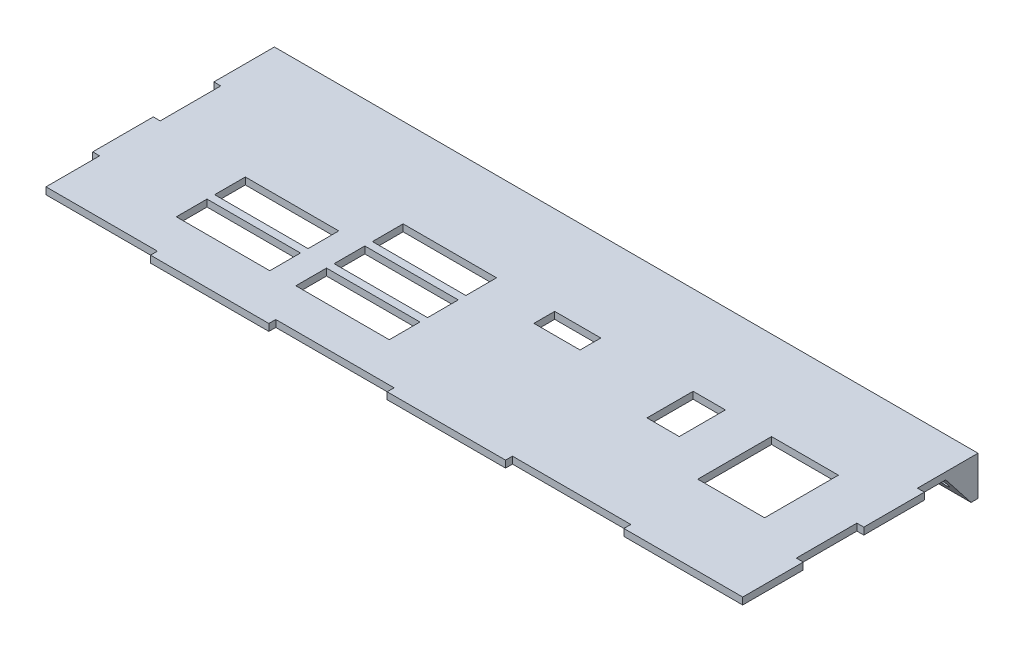
SolidWorks part; units mm, degrees
ref_plane "Спереди" through (0, 0, 0) normal (0, 0, 1) x (1, 0, 0)
ref_plane "Сверху" through (0, 0, 0) normal (0, 1, 0) x (1, 0, 0)
ref_plane "Справа" through (0, 0, 0) normal (1, 0, 0) x (0, 0, -1)
other "Configuration Table"
sketch "Эскиз1" plane through (0, 0, 0) normal (0, 1, 0) x (1, 0, 0)
  line L0 (-121.424, 15.1446) -> (-121.424, 41.3946)
  line L1 (-118.424, -63.6054) -> (186.576, -63.6054)
  line L2 (-121.424, -37.3554) -> (-121.424, -11.1054)
  line L3 (-121.424, 41.3946) -> (183.576, 41.3946)
  line L4 (186.576, -63.6054) -> (186.576, -37.3554)
  line L5 (-118.424, -62.7765) -> (183.576, 97.3135) construction
  line L6 (-121.424, 41.3946) -> (186.576, -63.6054) construction
  line L11 (-121.424, 15.1446) -> (-118.424, 15.1446)
  line L13 (-121.424, -11.1054) -> (-118.424, -11.1054)
  line L14 (-118.424, 15.1446) -> (-118.424, -11.1054)
  line L15 (-121.424, -37.3554) -> (-118.424, -37.3554)
  line L18 (-118.424, -37.3554) -> (-118.424, -63.6054)
  line L21 (186.576, 15.1446) -> (183.576, 15.1446)
  line L22 (183.576, 41.3946) -> (183.576, 15.1446)
  line L23 (186.576, -37.3554) -> (183.576, -37.3554)
  line L25 (186.576, -11.1054) -> (183.576, -11.1054)
  line L26 (183.576, -37.3554) -> (183.576, -11.1054)
  line L27 (186.576, -11.1054) -> (186.576, 15.1446)
  point P0 (0, 0)
  dimension "D1" = 308
  dimension "D2" = 105
  dimension "D3" = 26.25
  dimension "D4" = 26.25
  dimension "D5" = 3
extrude "Бобышка-Вытянуть1" add sketch "Эскиз1" along normal blind 3
sketch "Эскиз2" plane through (0, 3, 0) normal (0, 1, 0) x (1, 0, 0)
  line L0 (-118.424, -63.6054) -> (186.576, -63.6054) construction
  line L1 (-78.924, -43.6054) -> (-38.424, -43.6054)
  line L2 (-78.924, -43.6054) -> (-78.924, -30.3054)
  line L3 (-78.924, -30.3054) -> (-38.424, -30.3054)
  line L4 (-38.424, -43.6054) -> (-38.424, -30.3054)
  line L5 (-121.424, -11.1054) -> (-121.424, -37.3554) construction
  line L6 (-27.124, -43.6054) -> (13.376, -43.6054)
  line L7 (-27.124, -43.6054) -> (-27.124, -30.3054)
  line L8 (-27.124, -30.3054) -> (13.376, -30.3054)
  line L9 (13.376, -43.6054) -> (13.376, -30.3054)
  line L10 (-27.124, -27.0054) -> (13.376, -27.0054)
  line L11 (-27.124, -27.0054) -> (-27.124, -13.7054)
  line L12 (-27.124, -13.7054) -> (13.376, -13.7054)
  line L13 (13.376, -27.0054) -> (13.376, -13.7054)
  line L14 (-78.924, -27.0054) -> (-38.424, -27.0054)
  line L15 (-78.924, -27.0054) -> (-78.924, -13.7054)
  line L16 (-78.924, -13.7054) -> (-38.424, -13.7054)
  line L17 (-38.424, -27.0054) -> (-38.424, -13.7054)
  line L18 (-27.124, -10.4054) -> (13.376, -10.4054)
  line L19 (-27.124, -10.4054) -> (-27.124, 2.8946)
  line L20 (-27.124, 2.8946) -> (13.376, 2.8946)
  line L21 (13.376, -10.4054) -> (13.376, 2.8946)
  line L23 (38.576, -6.1054) -> (58.576, -6.1054)
  line L24 (38.576, -6.1054) -> (38.576, 2.8946)
  line L25 (38.576, 2.8946) -> (58.576, 2.8946)
  line L26 (58.576, -6.1054) -> (58.576, 2.8946)
  line L27 (38.576, -6.1054) -> (58.576, 2.8946) construction
  line L28 (38.576, 2.8946) -> (58.576, -6.1054) construction
  line L30 (98.576, -17.1054) -> (112.576, -17.1054)
  line L31 (98.576, -17.1054) -> (98.576, 2.8946)
  line L32 (98.576, 2.8946) -> (112.576, 2.8946)
  line L33 (112.576, -17.1054) -> (112.576, 2.8946)
  line L34 (98.576, -17.1054) -> (112.576, 2.8946) construction
  line L35 (98.576, 2.8946) -> (112.576, -17.1054) construction
  line L37 (132.576, -29.1054) -> (161.576, -29.1054)
  line L38 (132.576, -29.1054) -> (132.576, 2.8946)
  line L39 (132.576, 2.8946) -> (161.576, 2.8946)
  line L40 (161.576, -29.1054) -> (161.576, 2.8946)
  line L41 (132.576, -29.1054) -> (161.576, 2.8946) construction
  line L42 (132.576, 2.8946) -> (161.576, -29.1054) construction
  point P6 (-78.924, -36.9554)
  point P9 (48.576, -1.6054)
  point P30 (105.576, -7.1054)
  point P35 (147.076, -13.1054)
  dimension "D1" = 40.5
  dimension "D2" = 13.3
  dimension "D3" = 20
  dimension "D4" = 42.5
  dimension "D7" = 3.3
  dimension "D8" = 11.3
  dimension "D10" = 20
  dimension "D11" = 9
  dimension "D12" = 160
  dimension "D13" = 20
  dimension "D14" = 14
  dimension "D15" = 20
  dimension "D16" = 40
  dimension "D17" = 29
  dimension "D18" = 32
  dimension "D19" = 3.3
  dimension "D6" = 2
  dimension "D5" = 2
  dimension "D9" = 2
extrude "Вырез-Вытянуть1" cut sketch "Эскиз2" against normal blind 3
sketch "Эскиз3" plane through (0, 3, 0) normal (0, 1, 0) x (1, 0, 0)
  line L0 (-118.424, -63.6054) -> (186.576, -63.6054) construction
  line L1 (-70.124, -63.6054) -> (-121.424, -63.6054)
  line L2 (-70.124, -63.6054) -> (-70.124, -60.6054)
  line L3 (-70.124, -60.6054) -> (-121.424, -60.6054)
  line L4 (-121.424, -63.6054) -> (-121.424, -60.6054)
  line L5 (-121.424, -11.1054) -> (-121.424, -37.3554) construction
  line L7 (-18.824, -63.6054) -> (32.476, -63.6054)
  line L8 (-18.824, -63.6054) -> (-18.824, -60.6054)
  line L9 (-18.824, -60.6054) -> (32.476, -60.6054)
  line L10 (32.476, -63.6054) -> (32.476, -60.6054)
  line L11 (83.776, -63.6054) -> (135.076, -63.6054)
  line L12 (83.776, -63.6054) -> (83.776, -60.6054)
  line L13 (83.776, -60.6054) -> (135.076, -60.6054)
  line L14 (135.076, -63.6054) -> (135.076, -60.6054)
  dimension "D1" = 51.3
  dimension "D2" = 3
  dimension "D3" = 51.3
  dimension "D4" = 51.3
extrude "Вырез-Вытянуть2" cut sketch "Эскиз3" against normal blind 3
sketch "Эскиз4" plane through (0, 0, 0) normal (0, -1, 0) x (1, 0, 0)
  line L0 (-118.424, -15.1446) -> (-118.424, -41.3946) construction
  line L1 (183.576, -41.3946) -> (-121.424, -41.3946) construction
  line L2 (25.576, -13.3946) -> (29.576, -13.3946)
  line L3 (-118.424, -41.3946) -> (-104.424, -41.3946)
  line L4 (-118.424, -41.3946) -> (-118.424, -27.3946)
  line L5 (-118.424, -27.3946) -> (-104.424, -27.3946)
  line L6 (-104.424, -41.3946) -> (-104.424, -27.3946)
  line L7 (183.576, -41.3946) -> (169.576, -41.3946)
  line L8 (183.576, -41.3946) -> (183.576, -27.3946)
  line L9 (183.576, -27.3946) -> (169.576, -27.3946)
  line L10 (169.576, -41.3946) -> (169.576, -27.3946)
  line L11 (35.576, -13.3946) -> (39.576, -13.3946)
  line L13 (25.576, -41.3946) -> (29.576, -41.3946)
  line L14 (25.576, -41.3946) -> (25.576, -13.3946)
  line L16 (39.576, -41.3946) -> (39.576, -13.3946)
  line L17 (35.576, -13.3946) -> (35.576, -41.3946)
  line L19 (29.576, -13.3946) -> (29.576, -41.3946)
  line L20 (35.576, -41.3946) -> (39.576, -41.3946)
  dimension "D1" = 14
  dimension "D2" = 14
  dimension "D3" = 130
  dimension "D4" = 28
  dimension "D5" = 4
  dimension "D6" = 4
  dimension "D7" = 14
extrude "Бобышка-Вытянуть2" add sketch "Эскиз4" along normal blind 14
sketch "Эскиз6" plane through (39.576, 0, 0) normal (1, 0, 0) x (0, 0, -1)
  line L1 (41.3946, -14) -> (13.3946, -14) construction
  line L4 (13.3946, -14) -> (13.3946, 0)
  line L5 (13.3946, 0) -> (38.3946, -14)
  line L6 (13.3946, -14) -> (38.3946, -14)
  dimension "D1" = 25
extrude "Вырез-Вытянуть3" cut sketch "Эскиз6" against normal blind 14
sketch "Эскиз7" plane through (183.576, 0, 0) normal (1, 0, 0) x (0, 0, -1)
  line L0 (27.3946, -14) -> (27.3946, 0)
  line L1 (27.3946, -14) -> (38.3946, -14)
  line L2 (41.3946, -14) -> (27.3946, -14) construction
  line L3 (38.3946, -14) -> (27.3946, 0)
  dimension "D1" = 11
extrude "Вырез-Вытянуть4" cut sketch "Эскиз7" against normal blind 14
sketch "Эскиз8" plane through (-104.424, 0, 0) normal (1, 0, 0) x (0, 0, -1)
  line L0 (27.3946, -14) -> (27.3946, 0)
  line L1 (41.3946, 0) -> (13.3946, 0) construction
  line L2 (27.3946, 0) -> (38.3946, -14)
  line L3 (38.3946, -14) -> (27.3946, -14)
extrude "Вырез-Вытянуть5" cut sketch "Эскиз8" against normal blind 14
sketch "Эскиз9" plane through (0, 0, -41.3946) normal (0, 0, -1) x (-1, 0, 0)
  line L0 (-169.576, -14) -> (-183.576, -14) construction
  line L1 (-183.576, 3) -> (-183.576, -14) construction
  line L2 (118.424, -14) -> (104.424, -14) construction
  line L3 (104.424, -14) -> (104.424, 0) construction
  circle A0 centre (-176.576, -7) radius 2.5
  circle A1 centre (111.424, -7) radius 2.5
  dimension "D3" = 5
  dimension "D4" = 5
  dimension "D1" = 7
  dimension "D2" = 7
  dimension "D5" = 7
  dimension "D6" = 7
extrude "Вырез-Вытянуть6" cut sketch "Эскиз9" against normal up to vertex up to point (169.576, 0, -27.3945)
sketch "Эскиз5" plane through (183.576, 0, 0) normal (1, 0, 0) x (0, 0, -1)
  line L0 (27.3946, 0) -> (41.3946, 0) construction
  line L1 (27.3946, -14) -> (39.1457, -14)
  line L3 (41.3946, -14) -> (27.3946, -14) construction
